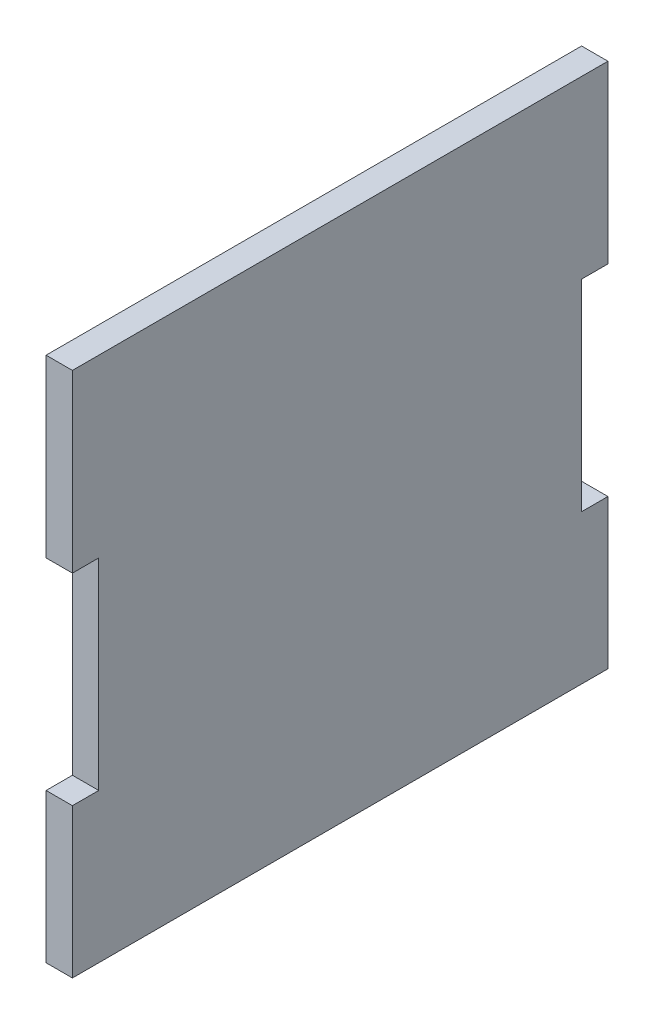
SolidWorks part; units mm, degrees
material "Acrilico TEC"
ref_plane "Front Plane" through (0, 0, 0) normal (0, 0, 1) x (1, 0, 0)
ref_plane "Top Plane" through (0, 0, 0) normal (0, 1, 0) x (1, 0, 0)
ref_plane "Right Plane" through (0, 0, 0) normal (1, 0, 0) x (0, 0, -1)
sketch "Sketch1" plane through (0, 0, 0) normal (1, 0, 0) x (0, 0, -1)
  line L0 (-27.5, 0) -> (27.5, 0)
  line L1 (-30.5, 39.94) -> (-30.5, 59.94)
  line L2 (27.5, 17) -> (30.5, 17)
  line L3 (-27.5, 17) -> (-27.5, 39.94)
  line L4 (30.5, 39.94) -> (27.5, 39.94)
  line L5 (-30.5, 0) -> (-30.5, 17)
  line L6 (27.5, 59.94) -> (-27.5, 59.94)
  line L7 (0, 59.94) -> (0, 0) construction
  line L8 (-30.5, 39.94) -> (-27.5, 39.94)
  line L9 (-27.5, 17) -> (-30.5, 17)
  line L10 (-30.5, 59.94) -> (-27.5, 59.94)
  line L11 (-30.5, 0) -> (-27.5, 0)
  line L13 (27.5, 0) -> (30.5, 0)
  line L14 (30.5, 0) -> (30.5, 17)
  line L15 (27.5, 17) -> (27.5, 39.94)
  line L16 (30.5, 39.94) -> (30.5, 59.94)
  line L17 (30.5, 59.94) -> (27.5, 59.94)
  dimension "D1" = 27.5
  dimension "D2" = 17
  dimension "D3" = 3
  dimension "D4" = 20
  dimension "D5" = 22.94
extrude "Boss-Extrude1" add sketch "Sketch1" along normal blind 3
